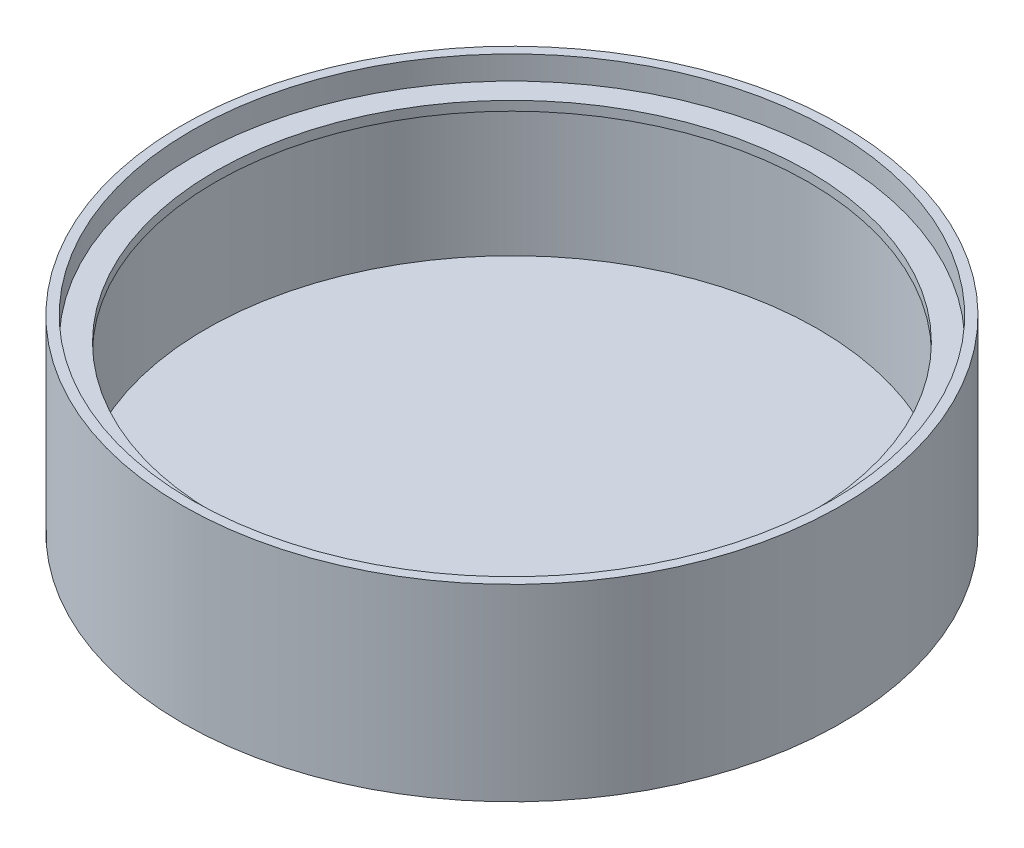
SolidWorks part; units mm, degrees
ref_plane "Front Plane" through (0, 0, 0) normal (0, 0, 1) x (1, 0, 0)
ref_plane "Top Plane" through (0, 0, 0) normal (0, 1, 0) x (1, 0, 0)
ref_plane "Right Plane" through (0, 0, 0) normal (1, 0, 0) x (0, 0, -1)
sketch "Sketch2" plane through (0, 0, 0) normal (0, 1, 0) x (1, 0, 0)
  circle A0 centre (0, 0) radius 70
extrude "Boss-Extrude1" add sketch "Sketch2" along normal blind 40
ref_plane "Plane1" through (0, 40, 0) normal (0, 1, 0) x (1, 0, 0)
sketch "Sketch4" plane through (0, 40, 0) normal (0, 1, 0) x (1, 0, 0)
  circle A0 centre (0, 0) radius 63
extrude "Cut-Extrude1" cut sketch "Sketch4" against normal blind 35 contours A0
sketch "Sketch5" plane through (0, 40, 0) normal (0, 1, 0) x (1, 0, 0)
  circle A0 centre (0, 0) radius 68
extrude "Cut-Extrude2" cut sketch "Sketch5" against normal blind 5 contours A0
ref_plane "Plane3" through (0, 33, 0) normal (0, 1, 0) x (1, 0, 0)
sketch "Sketch6" plane through (0, 33, 0) normal (0, 1, 0) x (1, 0, 0)
  circle A0 centre (0, 0) radius 65
extrude "Cut-Extrude3" cut sketch "Sketch6" against normal blind 28 contours A0
ref_plane "Plane4" through (0, 5, 0) normal (0, 1, 0) x (1, 0, 0)
sketch "Sketch7" plane through (0, 0, 0) normal (0, 1, 0) x (1, 0, 0)
  line L0 (0, 70) -> (0, -70)
  line L1 (70, 0) -> (-70, 0)
  line L2 (70, 0) -> (70, 7.5)
  line L3 (70, 0) -> (70, -7.5)
  line L4 (0, -70) -> (7.5, -70)
  line L5 (0, -70) -> (-7.5, -70)
  line L6 (-70, 0) -> (-70, -7.5)
  line L7 (-70, 0) -> (-70, 7.5)
  line L8 (0, 70) -> (-7.5, 70)
  line L9 (0, 70) -> (7.5, 70)
  circle A0 centre (0, 0) radius 70 construction
  point P21 (0, 0)
  dimension "D1" = 4
